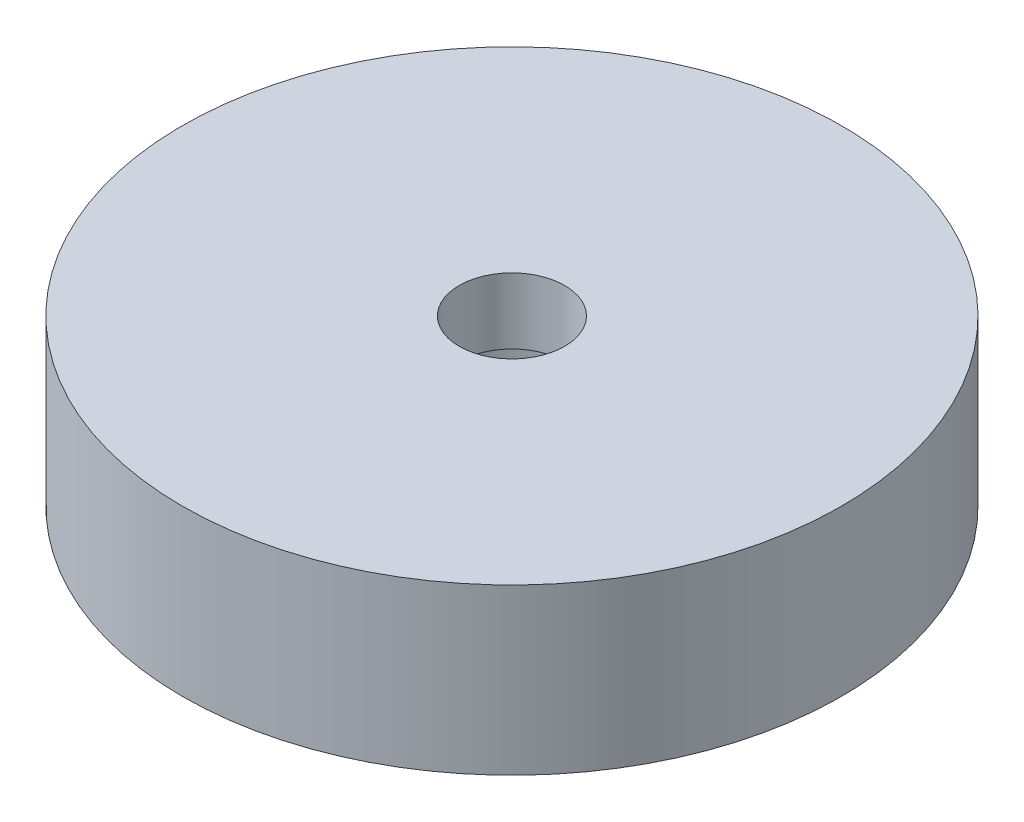
SolidWorks part; units mm, degrees
ref_plane "Front Plane" through (0, 0, 0) normal (0, 0, 1) x (1, 0, 0)
ref_plane "Top Plane" through (0, 0, 0) normal (0, 1, 0) x (1, 0, 0)
ref_plane "Right Plane" through (0, 0, 0) normal (1, 0, 0) x (0, 0, -1)
sketch "Sketch1" plane through (0, 0, 0) normal (0, 1, 0) x (1, 0, 0)
  circle A0 centre (0, 0) radius 10
  dimension "D1" = 20
extrude "Boss-Extrude1" add sketch "Sketch1" along normal blind 5
sketch "Sketch2" plane through (0, 5, 0) normal (0, 1, 0) x (1, 0, 0)
  circle A0 centre (0, 0) radius 3
  dimension "D1" = 6
extrude "Cut-Extrude1" cut sketch "Sketch2" against normal blind 5 from offset 2 offset against normal yes
sketch "Sketch3" plane through (0, 5, 0) normal (0, 1, 0) x (1, 0, 0)
  circle A0 centre (0, 0) radius 1.6
  dimension "D1" = 3.2
extrude "Cut-Extrude2" cut sketch "Sketch3" against normal through all
